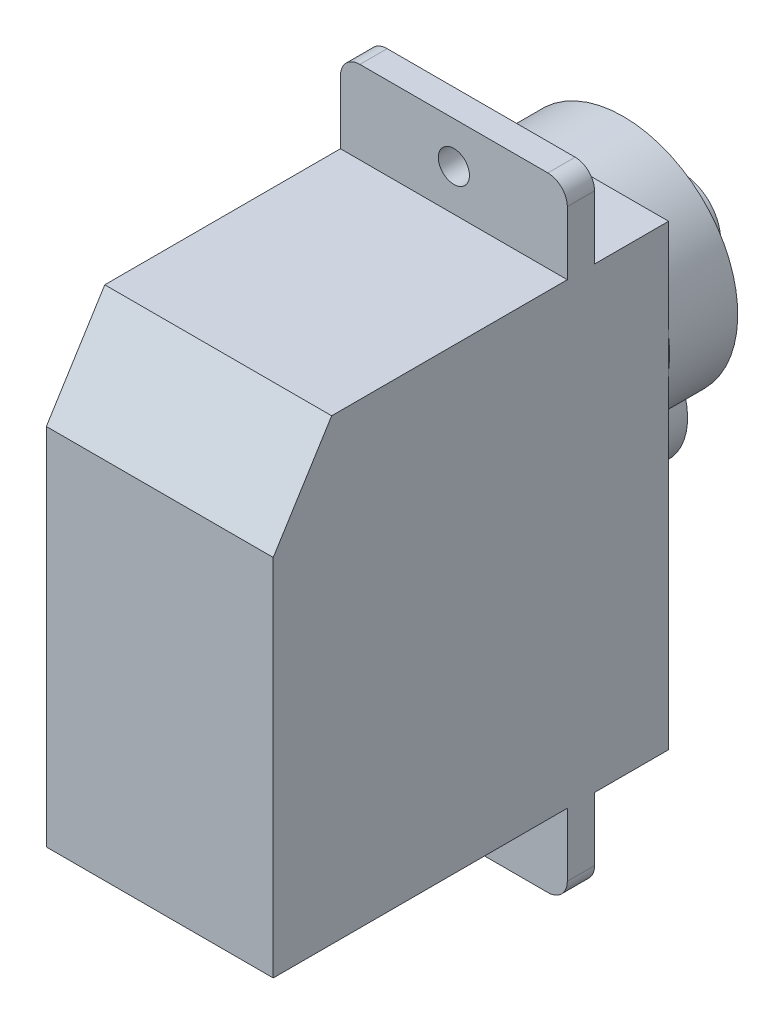
SolidWorks part; units mm, degrees
ref_plane "Спереди" through (0, 0, 0) normal (0, 0, 1) x (1, 0, 0)
ref_plane "Сверху" through (0, 0, 0) normal (0, 1, 0) x (1, 0, 0)
ref_plane "Справа" through (0, 0, 0) normal (1, 0, 0) x (0, 0, -1)
ref_plane "Плоскость4" through (-5.825, 0, 0) normal (-1, 0, 0) x (0, -1, 0)
sketch "Эскиз1" plane through (-5.825, 0, 0) normal (-1, 0, 0) x (0, -1, 0)
  line L0 (16, 0) -> (16, 20.3)
  line L1 (16, 20.3) -> (-16, 20.3)
  line L2 (-16, 20.3) -> (-16, 0)
  line L3 (-16, 0) -> (16, 0)
extrude "Бобышка-Вытянуть1" add sketch "Эскиз1" against normal blind 11.65
sketch "Эскиз2" plane through (0, 0, 0) normal (0, 0, -1) x (-1, 0, 0)
  arc A0 (-3.1672, 0.9268) -> (3.1672, 0.9268) centre (0, 5.875) cw
  arc A1 (3.1672, 0.9268) -> (-3.1672, 0.9268) centre (0, 0) cw
extrude "Бобышка-Вытянуть2" add sketch "Эскиз2" along normal blind 3.5
sketch "Эскиз3" plane through (-5.825, 0, 0) normal (-1, 0, 0) x (0, 0, 1)
  line L0 (0, 16) -> (0, 11.75)
  line L1 (0, 11.75) -> (3.8, 11.75)
  line L2 (3.8, 11.75) -> (3.8, 16)
  line L3 (3.8, 16) -> (0, 16)
extrude "Вырез-Вытянуть1" cut sketch "Эскиз3" against normal through all
sketch "Эскиз4" plane through (5.825, 0, 0) normal (1, 0, 0) x (0, 0, -1)
  line L0 (-3.8, -11.75) -> (-3.8, -16)
  line L1 (-3.8, -16) -> (0, -16)
  line L2 (0, -16) -> (0, -11.75)
  line L3 (0, -11.75) -> (-3.8, -11.75)
extrude "Вырез-Вытянуть2" cut sketch "Эскиз4" against normal through all
sketch "Эскиз5" plane through (5.825, 0, 0) normal (1, 0, 0) x (0, 0, -1)
  line L0 (-5.2, -11.75) -> (-20.3, -11.75)
  line L1 (-20.3, -11.75) -> (-20.3, -16)
  line L2 (-20.3, -16) -> (-5.2, -16)
  line L3 (-5.2, -16) -> (-5.2, -11.75)
extrude "Вырез-Вытянуть3" cut sketch "Эскиз5" against normal through all
sketch "Эскиз6" plane through (5.825, 0, 0) normal (1, 0, 0) x (0, 0, -1)
  line L0 (-5.2, 11.75) -> (-5.2, 16)
  line L1 (-5.2, 16) -> (-20.3, 16)
  line L2 (-20.3, 16) -> (-20.3, 11.75)
  line L3 (-20.3, 11.75) -> (-5.2, 11.75)
extrude "Вырез-Вытянуть4" cut sketch "Эскиз6" against normal through all
ref_plane "Плоскость5" through (0, 5.75, 0) normal (0, -1, 0) x (1, 0, 0)
sketch "Эскиз7" plane through (0, 5.75, 0) normal (0, -1, 0) x (1, 0, 0)
  line L0 (2, -3.5) -> (0, -3.5)
  line L1 (0, -3.5) -> (0, -6.5)
  line L2 (0, -6.5) -> (2, -6.5)
  line L3 (2, -6.5) -> (2, -3.5)
  line L4 (0, -3.5) -> (0, -6.5) construction
revolve "Повернуть1" add sketch "Эскиз7" angle 360 about L4
ref_plane "Плоскость6" through (0, 0, 0) normal (0, -1, 0) x (1, 0, 0)
sketch "Эскиз8" plane through (0, 0, 0) normal (0, -1, 0) x (1, 0, 0)
  line L0 (1, -3.5) -> (0, -3.5)
  line L1 (0, -3.5) -> (0, -4.5)
  line L2 (0, -4.5) -> (1, -4.5)
  line L3 (1, -4.5) -> (1, -3.5)
  line L4 (0, -3.5) -> (0, -4.5) construction
revolve "Повернуть2" add sketch "Эскиз8" angle 360 about L4
hole_wizard "Диаметр отверстия Ø1.6 (1.6)1" positions "Эскиз10" profile "Эскиз9" hole size "Ø1.6" standard "Ansi Metric"
sketch "Эскиз10" plane through (0, 0, 5.2) normal (0, 0, 1) x (1, 0, 0)
  point P0 (0, -13.875)
  point P1 (0, 13.875)
sketch "Эскиз9" plane through (0, -13.875, 5.2) normal (1, 0, 0) x (0, -1, 0)
  line L0 (0, 0) -> (0, 11.7)
  line L1 (0, 11.7) -> (0.8, 11.7)
  line L2 (0.8, 11.7) -> (0.8, 0)
  line L5 (0.8, 0) -> (0, 0)
  line L11 (0, -6.35) -> (0, 107.95) construction
  dimension "Диаметр сквозного отверстия" = 1.6
  dimension "Глубина сквозного отверстия" = 11.7
chamfer "Фаска1" distance 3 angle 57.995 1 edges at (0, 11.75, 20.3)
fillet "Скругление1" radius 1 4 edges at (5.825, 16, 4.5) (5.825, -16, 4.5) (-5.825, -16, 4.5) (-5.825, 16, 4.5)
sketch "Эскиз11" plane through (0, 0, -6.5) normal (0, 0, -1) x (-1, 0, 0)
  point P0 (0, 5.75)
